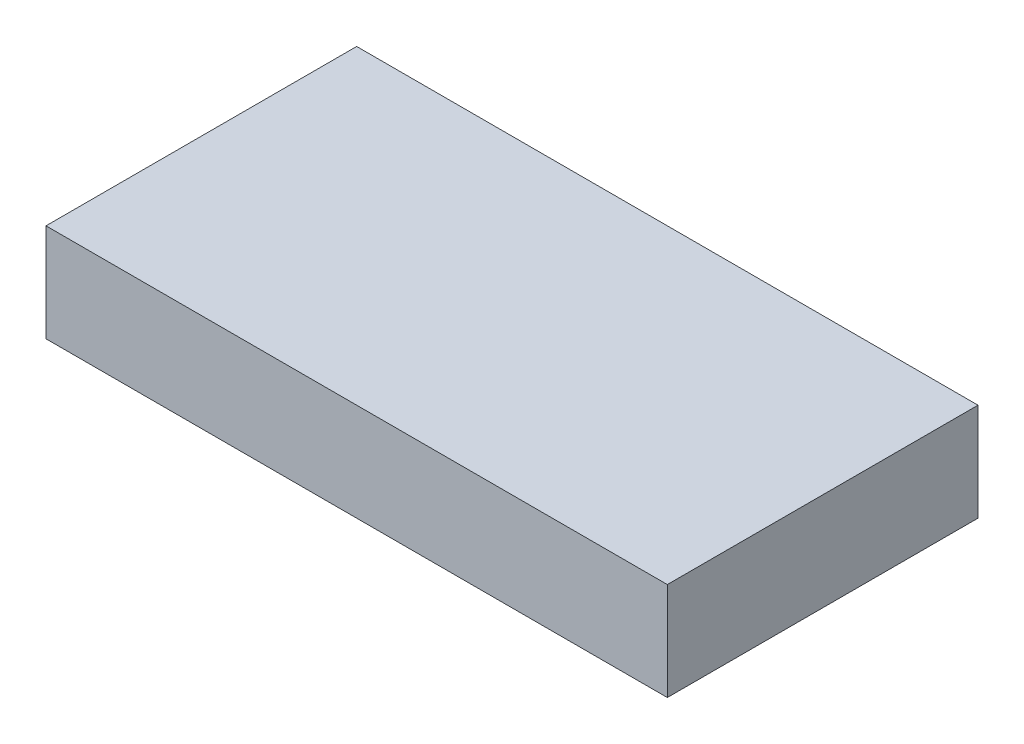
SolidWorks part; units mm, degrees
ref_plane "Front Plane" through (0, 0, 0) normal (0, 0, 1) x (1, 0, 0)
ref_plane "Top Plane" through (0, 0, 0) normal (0, 1, 0) x (1, 0, 0)
ref_plane "Right Plane" through (0, 0, 0) normal (1, 0, 0) x (0, 0, -1)
sketch "Sketch1" plane through (0, 0, 0) normal (0, 1, 0) x (1, 0, 0)
  line L1 (0, 0) -> (40, 0)
  line L2 (0, 0) -> (0, 20)
  line L3 (0, 20) -> (40, 20)
  line L4 (40, 0) -> (40, 20)
extrude "Boss-Extrude1" add sketch "Sketch1" along normal blind 6.3
